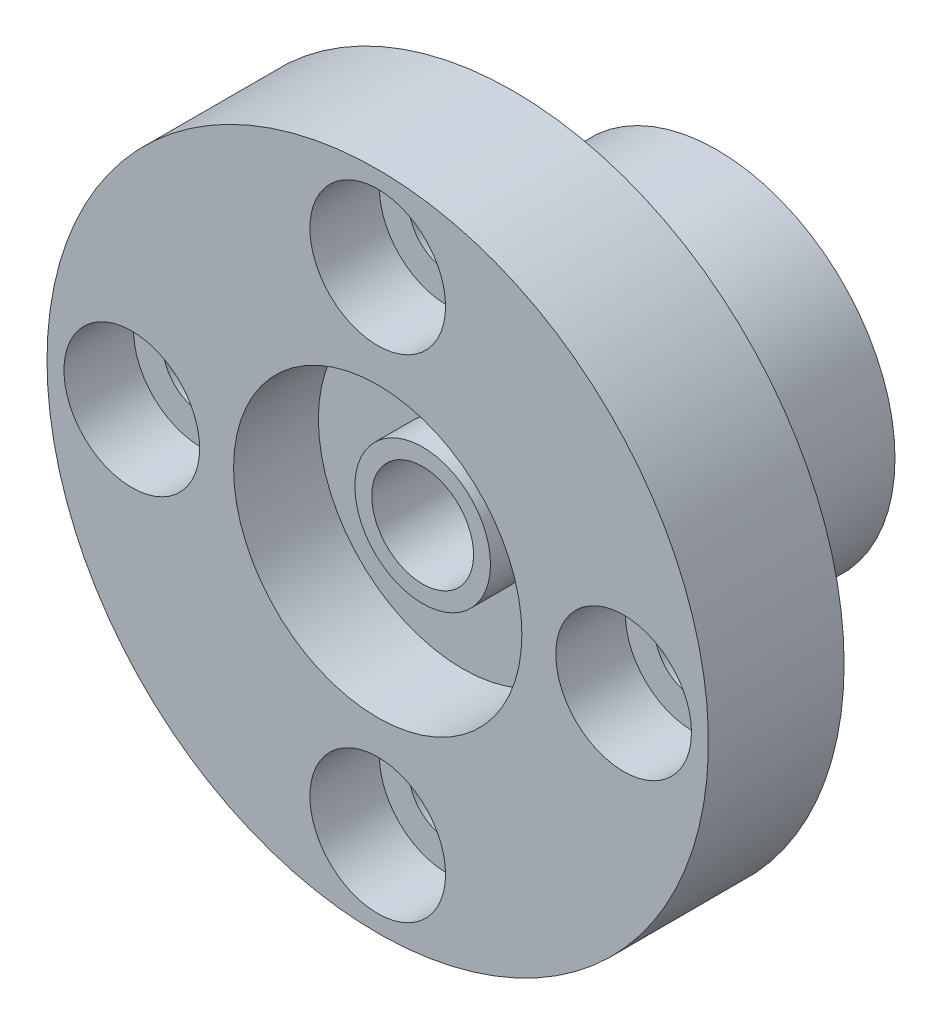
SolidWorks part; units mm, degrees
ref_plane "前视基准面" through (0, 0, 0) normal (0, 0, 1) x (1, 0, 0)
ref_plane "上视基准面" through (0, 0, 0) normal (0, 1, 0) x (1, 0, 0)
ref_plane "右视基准面" through (0, 0, 0) normal (1, 0, 0) x (0, 0, -1)
sketch "草图1" plane through (0, 0, 0) normal (0, 0, 1) x (1, 0, 0)
  circle A0 centre (0, 0) radius 19.5
  circle A1 centre (0, 0) radius 9.5
  circle A2 centre (0, 0) radius 5
extrude "凸台-拉伸1" add sketch "草图1" along normal blind 6 contours A0
sketch "草图2" plane through (0, 0, 0) normal (0, 0, -1) x (-1, 0, 0)
  circle A0 centre (0, 0) radius 9.5
extrude "凸台-拉伸2" add sketch "草图2" along normal blind 3
sketch "草图3" plane through (0, 0, -3) normal (0, 0, -1) x (-1, 0, 0)
  circle A0 centre (0, 0) radius 5
extrude "切除-拉伸1" cut sketch "草图3" against normal blind 50
sketch "草图4" plane through (0, 0, 6) normal (0, 0, 1) x (1, 0, 0)
  circle A1 centre (0, 14.5) radius 4
  circle A2 centre (14.5, 0) radius 4
  circle A3 centre (0, -14.5) radius 4
  circle A4 centre (-14.5, 0) radius 4
extrude "切除-拉伸2" cut sketch "草图4" against normal blind 4.4
sketch "草图5" plane through (0, 0, 1.6) normal (0, 0, 1) x (1, 0, 0)
  circle A0 centre (-14.5, 0) radius 2.25
extrude "切除-拉伸3" cut sketch "草图5" against normal blind 4.4
sketch "草图6" plane through (0, 0, 1.6) normal (0, 0, 1) x (1, 0, 0)
  circle A0 centre (0, 14.5) radius 2.25
extrude "切除-拉伸4" cut sketch "草图6" against normal blind 4.4
sketch "草图7" plane through (0, 0, 1.6) normal (0, 0, 1) x (1, 0, 0)
  circle A0 centre (14.5, 0) radius 2.25
  circle A1 centre (0, -14.5) radius 2.25
extrude "切除-拉伸5" cut sketch "草图7" against normal blind 4.4
sketch "草图8" plane through (0, 0, 0) normal (0, 0, -1) x (-1, 0, 0)
  circle A0 centre (0, 0) radius 10.5
extrude "凸台-拉伸3" add sketch "草图8" along normal blind 12
sketch "草图9" plane through (0, 0, -12) normal (0, 0, -1) x (-1, 0, 0)
  circle A0 centre (0, 0) radius 8.5
extrude "切除-拉伸6" cut sketch "草图9" against normal blind 20
sketch "草图10" plane through (0, 0, 0) normal (0, 0, -1) x (-1, 0, 0)
  circle A0 centre (0, 0) radius 19.5
extrude "凸台-拉伸4" add sketch "草图10" against normal blind 8
sketch "草图11" plane through (0, 0, 8) normal (0, 0, 1) x (1, 0, 0)
  circle A0 centre (0, 0) radius 8.5
extrude "切除-拉伸8" cut sketch "草图11" against normal blind 8
sketch "草图12" plane through (0, 0, 8) normal (0, 0, 1) x (1, 0, 0)
  circle A1 centre (0, 14.5) radius 4
  circle A2 centre (14.5, 0) radius 4
  circle A3 centre (0, -14.5) radius 4
  circle A4 centre (-14.5, 0) radius 4
extrude "切除-拉伸10" cut sketch "草图12" against normal blind 4.1
sketch "草图13" plane through (0, 0, 3.9) normal (0, 0, 1) x (1, 0, 0)
  circle A0 centre (0, 14.5) radius 2.25
  circle A1 centre (14.5, 0) radius 2.25
  circle A2 centre (0, -14.5) radius 2.25
  circle A3 centre (-14.5, 0) radius 2.25
extrude "切除-拉伸11" cut sketch "草图13" against normal blind 4.1
sketch "草图14" plane through (0, 0, 8) normal (0, 0, 1) x (1, 0, 0)
  circle A0 centre (0, 0) radius 8.5
extrude "凸台-拉伸5" add sketch "草图14" against normal blind 20
sketch "草图15" plane through (0, 0, -12) normal (0, 0, -1) x (-1, 0, 0)
  circle A0 centre (0, 0) radius 8.5
extrude "切除-拉伸12" cut sketch "草图15" against normal blind 5
sketch "草图17" plane through (0, 0, -7) normal (0, 0, -1) x (-1, 0, 0)
  circle A1 centre (0, 0) radius 4
extrude "凸台-拉伸7" add sketch "草图17" along normal blind 2.35
sketch "草图18" plane through (0, 0, -9.35) normal (0, 0, -1) x (-1, 0, 0)
  circle A0 centre (0, 0) radius 3
extrude "切除-拉伸13" cut sketch "草图18" against normal blind 20
sketch "草图19" plane through (0, 0, 8) normal (0, 0, 1) x (1, 0, 0)
  circle A0 centre (0, 0) radius 8.5
extrude "切除-拉伸14" cut sketch "草图19" against normal blind 5
sketch "草图20" plane through (0, 0, 3) normal (0, 0, 1) x (1, 0, 0)
  circle A0 centre (0, 0) radius 4
extrude "凸台-拉伸8" add sketch "草图20" along normal blind 2.35
sketch "草图21" plane through (0, 0, 5.35) normal (0, 0, 1) x (1, 0, 0)
  circle A0 centre (0, 0) radius 3
extrude "切除-拉伸15" cut sketch "草图21" against normal blind 2.35
